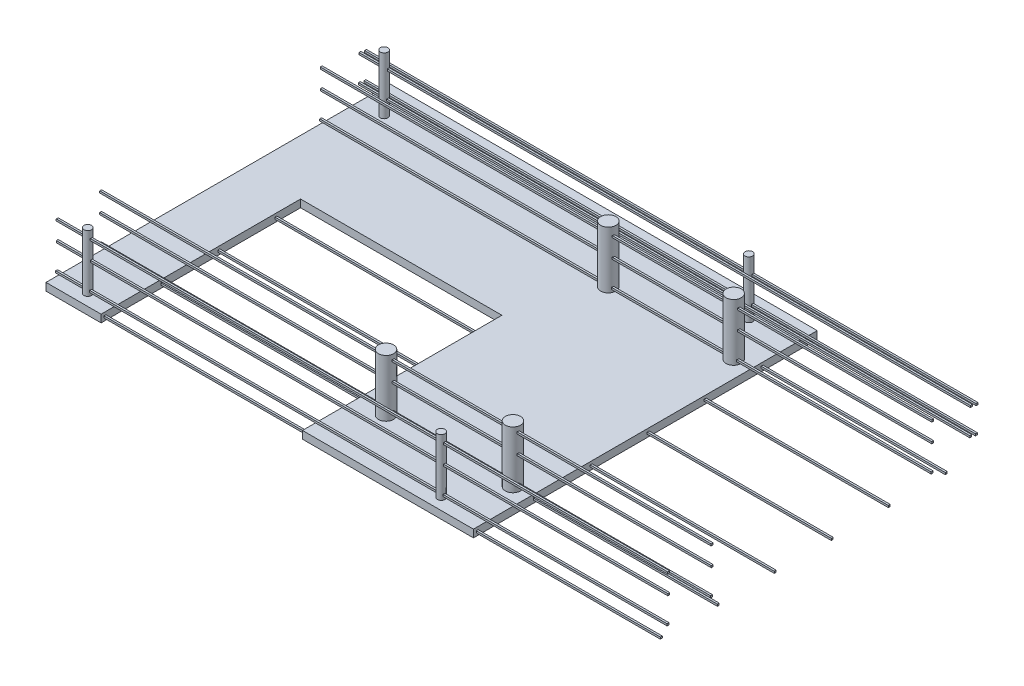
SolidWorks part; units mm, degrees
ref_plane "정면" through (0, 0, 0) normal (0, 0, 1) x (1, 0, 0)
ref_plane "윗면" through (0, 0, 0) normal (0, 1, 0) x (1, 0, 0)
ref_plane "우측면" through (0, 0, 0) normal (1, 0, 0) x (0, 0, -1)
sketch "스케치1" plane through (0, 0, 0) normal (0, 1, 0) x (1, 0, 0)
  line L1 (-60, 60) -> (60, 60)
  line L2 (-60, 60) -> (-60, -60)
  line L3 (-60, -60) -> (60, -60)
  line L4 (60, 60) -> (60, -60)
  line L5 (-60, 60) -> (60, -60) construction
  line L6 (-60, -60) -> (60, 60) construction
  point P0 (0, 0)
  dimension "D1" = 120
  dimension "D2" = 120
extrude "보스-돌출1" add sketch "스케치1" along normal blind 2
sketch "스케치2" plane through (0, 2, 0) normal (0, 1, 0) x (1, 0, 0)
  circle A0 centre (55.5, 24.5) radius 2
  circle A1 centre (55.5, -33.6) radius 2
  circle A2 centre (48.5, -45.5) radius 1
  circle A3 centre (22.5, -34) radius 2
  circle A4 centre (22.5, 24.5) radius 2
  circle A5 centre (48.5, 35.5) radius 1
  circle A6 centre (-46, 34) radius 1
  circle A7 centre (-44.5, -45.5) radius 1
  dimension "D1" = 4
  dimension "D2" = 4
  dimension "D3" = 2
  dimension "D4" = 4
  dimension "D5" = 4
  dimension "D6" = 2
  dimension "D7" = 2
  dimension "D8" = 2
extrude "보스-돌출2" add sketch "스케치2" along normal blind 15
sketch "스케치3" plane through (0, 2, 0) normal (0, 1, 0) x (1, 0, 0)
  line L0 (-60, -60) -> (60, -60) construction
  line L1 (60, 60) -> (15, 60)
  line L2 (60, 60) -> (60, -60)
  line L3 (60, -60) -> (15, -60)
  line L4 (15, 60) -> (15, -60)
  line L5 (-60, 60) -> (-60, -60) construction
  line L6 (-60, 29) -> (15, 29)
  line L7 (-60, 29) -> (-60, 60)
  line L8 (-60, 60) -> (15, 60)
  line L9 (15, 29) -> (15, 60)
  line L10 (-52.5, -60) -> (-52.5, 60)
  line L11 (-60, 60) -> (-38, 60)
  line L14 (-38, 60) -> (-38, -60)
  line L15 (-60, 42) -> (60, 42)
  circle A0 centre (-44.5, -45.5) radius 1 construction
  circle A1 centre (-46, 34) radius 1 construction
  circle A2 centre (22.5, 24.5) radius 2 construction
  circle A3 centre (48.5, 35.5) radius 1 construction
  line M10 (60, 60) -> (-60, 60)
  line M11 (-60, 60) -> (-60, -60)
  line M12 (-60, -60) -> (60, -60)
  dimension "D1" = 6.5
  dimension "D2" = 6.5
  dimension "D5" = 6.5
  dimension "D3" = 5
  dimension "D4" = 7.5
extrude "컷-돌출3" cut sketch "스케치3" against normal blind 15 contours L14 L15 L4 M10 | L4 L15 L2 M10 | L10 L15 L14 L8 | L15 L10 L8 M11 | L15 L7 L6 L10 | L10 L6 M12 M11
sketch "스케치4" plane through (0, 2, 0) normal (0, 1, 0) x (1, 0, 0)
  line L0 (-52.5, -60) -> (60, -60) construction
  line L1 (-38, 4) -> (15, 4)
  line L2 (-38, 4) -> (-38, -60)
  line L3 (-38, -60) -> (15, -60)
  line L4 (15, 4) -> (15, -60)
  circle A0 centre (-46, 34) radius 1 construction
  circle A1 centre (22.5, -34) radius 2 construction
  circle A2 centre (-44.5, -45.5) radius 1 construction
  dimension "D1" = 30
  dimension "D2" = 7.5
  dimension "D3" = 6.5
extrude "컷-돌출4" cut sketch "스케치4" against normal blind 15
sketch "스케치5" plane through (0, 2, 0) normal (0, 1, 0) x (1, 0, 0)
  line L0 (60, -48.5) -> (-52.5, -48.5)
  line L1 (60, -60) -> (60, 42) construction
  line L2 (-52.5, -60) -> (-52.5, 42) construction
  circle A0 centre (-44.5, -45.5) radius 1 construction
  line M1 (-38, -60) -> (-38, 4)
  line M3 (15, 4) -> (15, -60)
  line M4 (15, -60) -> (60, -60)
  line M5 (60, -60) -> (60, 42)
  line M7 (-52.5, 42) -> (-52.5, -60)
  line M8 (-52.5, -60) -> (-38, -60)
  dimension "D1" = 3
extrude "컷-돌출5" cut sketch "스케치5" against normal blind 10 and the other way through all contours L0 M5 M3 M4 | L0 M1 M7 M8
sketch "스케치7" plane through (60, 0, 0) normal (1, 0, 0) x (0, 0, -1)
  line L0 (-48.5, 2) -> (42, 2) construction
  line L1 (-47.75, 1.25) -> (-47.25, 1.25)
  line L2 (-47.75, 1.25) -> (-47.75, 0.75)
  line L3 (-47.75, 0.75) -> (-47.25, 0.75)
  line L4 (-47.25, 1.25) -> (-47.25, 0.75)
  line L5 (-48.5, 2) -> (-48.5, 0) construction
  line L10 (-32.75, 1.25) -> (-32.25, 1.25)
  line L11 (-32.75, 1.25) -> (-32.75, 0.75)
  line L12 (-32.75, 0.75) -> (-32.25, 0.75)
  line L13 (-32.25, 1.25) -> (-32.25, 0.75)
  line L14 (-17.75, 1.25) -> (-17.25, 1.25)
  line L15 (-17.75, 1.25) -> (-17.75, 0.75)
  line L16 (-17.75, 0.75) -> (-17.25, 0.75)
  line L17 (-17.25, 1.25) -> (-17.25, 0.75)
  line L18 (-2.75, 1.25) -> (-2.25, 1.25)
  line L19 (-2.75, 1.25) -> (-2.75, 0.75)
  line L20 (-2.75, 0.75) -> (-2.25, 0.75)
  line L21 (-2.25, 1.25) -> (-2.25, 0.75)
  line L22 (12.25, 1.25) -> (12.75, 1.25)
  line L23 (12.25, 1.25) -> (12.25, 0.75)
  line L24 (12.25, 0.75) -> (12.75, 0.75)
  line L25 (12.75, 1.25) -> (12.75, 0.75)
  line L26 (27.25, 1.25) -> (27.75, 1.25)
  line L27 (27.25, 1.25) -> (27.25, 0.75)
  line L28 (27.25, 0.75) -> (27.75, 0.75)
  line L29 (27.75, 1.25) -> (27.75, 0.75)
  dimension "D1" = 0.5
  dimension "D2" = 0.5
  dimension "D3" = 0.75
  dimension "D4" = 0.75
  dimension "D5" = 6
extrude "보스-돌출3" add sketch "스케치7" along normal up to surface and the other way up to surface
sketch "스케치8" plane through (60, 0, 0) normal (1, 0, 0) x (0, 0, -1)
  line L0 (-45.7944, 10.1749) -> (-45.2944, 10.1749)
  line L1 (-45.9591, 3.3776) -> (-45.4591, 3.3776)
  line L2 (-45.9591, 3.3776) -> (-45.9591, 2.8776)
  line L3 (-45.9591, 2.8776) -> (-45.4591, 2.8776)
  line L4 (-45.4591, 3.3776) -> (-45.4591, 2.8776)
  line L5 (-45.7944, 10.1749) -> (-45.7944, 9.6749)
  line L6 (-45.7944, 9.6749) -> (-45.2944, 9.6749)
  line L7 (-45.2944, 10.1749) -> (-45.2944, 9.6749)
  line L8 (-45.8054, 15.1287) -> (-45.3054, 15.1287)
  line L9 (-45.8054, 15.1287) -> (-45.8054, 14.6287)
  line L10 (-45.8054, 14.6287) -> (-45.3054, 14.6287)
  line L11 (-45.3054, 15.1287) -> (-45.3054, 14.6287)
  line L12 (-34.3599, 10.8482) -> (-33.8599, 10.8482)
  line L13 (-34.5247, 4.0508) -> (-34.0247, 4.0508)
  line L14 (-34.5247, 4.0508) -> (-34.5247, 3.5508)
  line L15 (-34.5247, 3.5508) -> (-34.0247, 3.5508)
  line L16 (-34.0247, 4.0508) -> (-34.0247, 3.5508)
  line L17 (-34.3599, 10.8482) -> (-34.3599, 10.3482)
  line L18 (-34.3599, 10.3482) -> (-33.8599, 10.3482)
  line L19 (-33.8599, 10.8482) -> (-33.8599, 10.3482)
  line L20 (-34.371, 15.8019) -> (-33.871, 15.8019)
  line L21 (-34.371, 15.8019) -> (-34.371, 15.3019)
  line L22 (-34.371, 15.3019) -> (-33.871, 15.3019)
  line L23 (-33.871, 15.8019) -> (-33.871, 15.3019)
  line L24 (23.7032, 10.0517) -> (24.2032, 10.0517)
  line L25 (23.5384, 3.2544) -> (24.0384, 3.2544)
  line L26 (23.5384, 3.2544) -> (23.5384, 2.7544)
  line L27 (23.5384, 2.7544) -> (24.0384, 2.7544)
  line L28 (24.0384, 3.2544) -> (24.0384, 2.7544)
  line L29 (23.7032, 10.0517) -> (23.7032, 9.5517)
  line L30 (23.7032, 9.5517) -> (24.2032, 9.5517)
  line L31 (24.2032, 10.0517) -> (24.2032, 9.5517)
  line L32 (23.6921, 15.0055) -> (24.1921, 15.0055)
  line L33 (23.6921, 15.0055) -> (23.6921, 14.5055)
  line L34 (23.6921, 14.5055) -> (24.1921, 14.5055)
  line L35 (24.1921, 15.0055) -> (24.1921, 14.5055)
  line L36 (33.87, 13.2228) -> (34.37, 13.2228)
  line L37 (33.7052, 6.4255) -> (34.2052, 6.4255)
  line L38 (33.7052, 6.4255) -> (33.7052, 5.9255)
  line L39 (33.7052, 5.9255) -> (34.2052, 5.9255)
  line L40 (34.2052, 6.4255) -> (34.2052, 5.9255)
  line L41 (33.87, 13.2228) -> (33.87, 12.7228)
  line L42 (33.87, 12.7228) -> (34.37, 12.7228)
  line L43 (34.37, 13.2228) -> (34.37, 12.7228)
  line L48 (35.3578, 12.9103) -> (35.8578, 12.9103)
  line L49 (35.193, 6.113) -> (35.693, 6.113)
  line L50 (35.193, 6.113) -> (35.193, 5.613)
  line L51 (35.193, 5.613) -> (35.693, 5.613)
  line L52 (35.693, 6.113) -> (35.693, 5.613)
  line L53 (35.3578, 12.9103) -> (35.3578, 12.4103)
  line L54 (35.3578, 12.4103) -> (35.8578, 12.4103)
  line L55 (35.8578, 12.9103) -> (35.8578, 12.4103)
  dimension "D1" = 0.5
  dimension "D2" = 0.5
  dimension "D3" = 0.5
  dimension "D4" = 0.5
  dimension "D5" = 0.5
  dimension "D6" = 0.5
  dimension "D7" = 0.5
  dimension "D8" = 0.5
  dimension "D9" = 0.5
  dimension "D11" = 0.5
extrude "보스-돌출4" add sketch "스케치8" along normal up to surface and the other way up to surface
